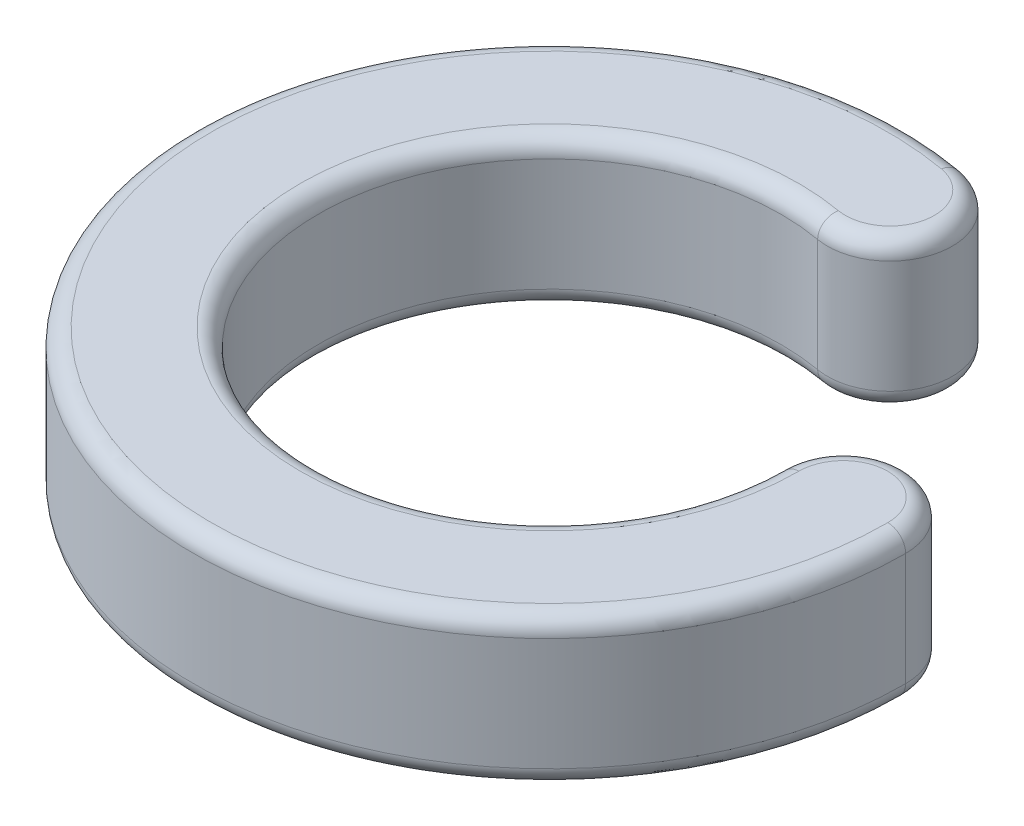
SolidWorks part; units mm, degrees
ref_plane "Front Plane" through (0, 0, 0) normal (0, 0, 1) x (1, 0, 0)
ref_plane "Top Plane" through (0, 0, 0) normal (0, 1, 0) x (1, 0, 0)
ref_plane "Right Plane" through (0, 0, 0) normal (1, 0, 0) x (0, 0, -1)
sketch "Sketch1" plane through (0, 0, 0) normal (0, 1, 0) x (1, 0, 0)
  arc A0 (3.9, 0) -> (0.6772, 3.8408) centre (0, 0) cw
  arc A1 (1.0419, 5.9088) -> (6, 0) centre (0, 0) ccw
  arc A2 (0.6772, 3.8408) -> (1.0419, 5.9088) centre (0.8596, 4.8748) ccw
  arc A3 (6, 0) -> (3.9, 0) centre (4.95, 0) ccw
  dimension "D1" = 3.9
  dimension "D2" = 6
extrude "Boss-Extrude1" add sketch "Sketch1" along normal blind 2.5
fillet "Fillet2" radius 0.3 4 edges at (1.8936, 2.5, -4.6925) (-2.9876, 2.5, 2.5069) (4.95, 2.5, -1.05) (-4.5963, 2.5, 3.8567)
fillet "Fillet3" radius 0.3 4 edges at (1.8936, 0, -4.6925) (-4.5963, 0, 3.8567) (4.95, 0, -1.05) (-2.9876, 0, 2.5069)
